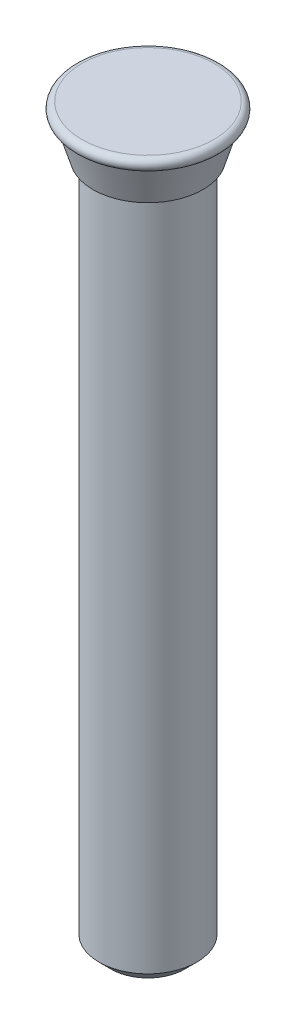
SolidWorks part; units mm, degrees
ref_plane "Front" through (0, 0, 0) normal (0, 0, 1) x (1, 0, 0)
ref_plane "Top" through (0, 0, 0) normal (0, 1, 0) x (1, 0, 0)
ref_plane "Right" through (0, 0, 0) normal (1, 0, 0) x (0, 0, -1)
ref_plane "Plane1" through (0, 0, 0) normal (0, 0, -1) x (-1, 0, 0)
sketch "Sketch1" plane through (0, 0, 0) normal (0, 0, -1) x (-1, 0, 0)
  line L0 (-1.5, -30) -> (0, -30)
  line L1 (0, -30) -> (0, 0)
  line L2 (0, 0) -> (-2.7, 0)
  line L3 (-2.7, -0.5) -> (-2.25, -2)
  line L4 (-2.25, -2) -> (-2, -2)
  line L5 (-2, -2) -> (-2, -29.5)
  line L6 (-2, -29.5) -> (-1.5, -30)
  line L7 (0, -30) -> (0, 0.0141) construction
  line L8 (0, 7.5379) -> (0, -38.3307) construction
  arc A0 (-2.7, 0) -> (-2.7, -0.5) centre (-2.7, -0.25) ccw
  dimension "D5" = 0.25
  dimension "D1" = 4
  dimension "D2" = 28
  dimension "D3" = 2
  dimension "D4" = 2.7
  dimension "D6" = 4.5
  dimension "D7" = 45
  dimension "D8" = 0.5
revolve "Revolve1" add sketch "Sketch1" angle 360 about L7
cosmetic thread "Cosmetic Thread1"
